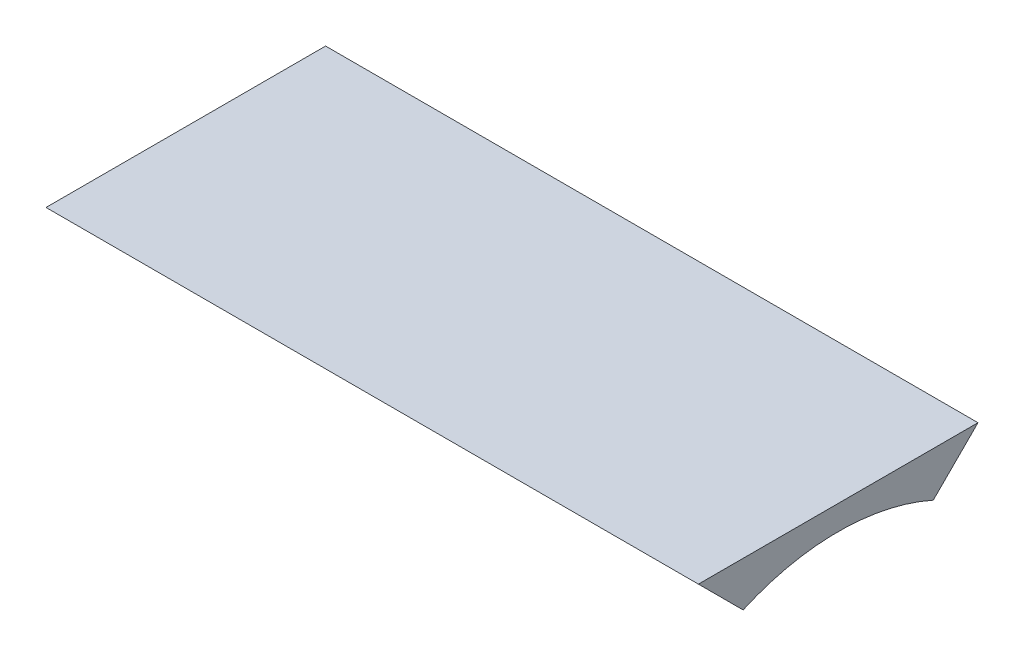
SolidWorks part; units mm, degrees
ref_plane "Front" through (0, 0, 0) normal (0, 0, 1) x (1, 0, 0)
ref_plane "Top" through (0, 0, 0) normal (0, 1, 0) x (1, 0, 0)
ref_plane "Right" through (0, 0, 0) normal (1, 0, 0) x (0, 0, -1)
sketch "Эскиз1" plane through (0, 0, 0) normal (1, 0, 0) x (0, 0, -1)
  line L0 (-10.2, 22.8245) -> (-15, 27.6245)
  line L1 (-15, 27.6245) -> (15, 27.6245)
  line L2 (15, 27.6245) -> (10.2, 22.8245)
  circle A0 centre (0, 0) radius 25
  dimension "D1" = 50
  dimension "D2" = 45
  dimension "D3" = 45
  dimension "D4" = 30
  dimension "D5" = 15
  dimension "D6" = 4.8
extrude "Бобышка-Вытянуть1" add sketch "Эскиз1" along normal blind 70 contours A0 L2 L1 L0
